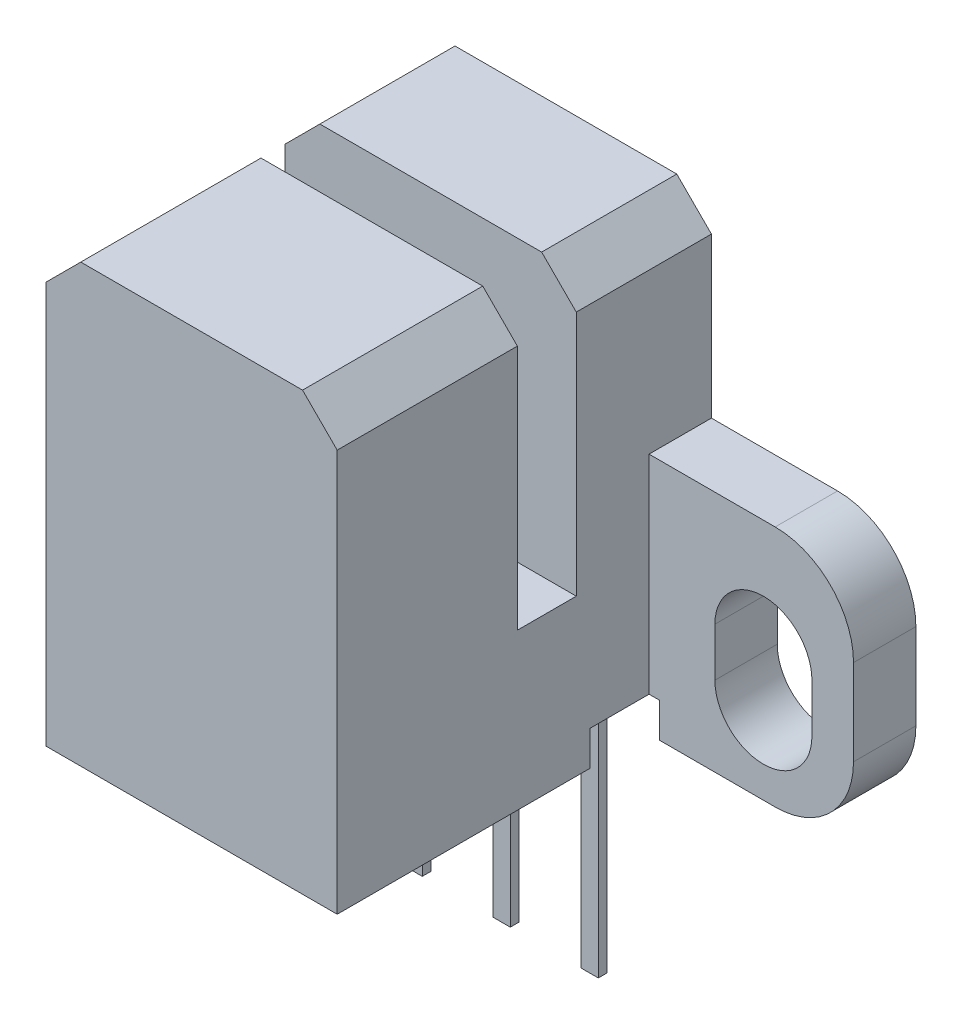
SolidWorks part; units mm, degrees
ref_plane "Front Plane" through (0, 0, 0) normal (0, 0, 1) x (1, 0, 0)
ref_plane "Top Plane" through (0, 0, 0) normal (0, 1, 0) x (1, 0, 0)
ref_plane "Right Plane" through (0, 0, 0) normal (1, 0, 0) x (0, 0, -1)
sketch "Sketch1" plane through (0, 0, 0) normal (0, 0, 1) x (1, 0, 0)
  line L0 (0, -8.7) -> (0, 3.9) construction
  line L1 (-4.2, -8.7) -> (4.2, -8.7)
  line L2 (-4.2, -8.7) -> (-4.2, 3.9)
  line L3 (-4.2, 3.9) -> (4.2, 3.9)
  line L4 (4.2, -8.7) -> (4.2, 3.9)
  dimension "D1" = 4.2
  dimension "D2" = 3.9
  dimension "D3" = 8.7
extrude "Boss-Extrude1" add sketch "Sketch1" along normal blind 10.8
chamfer "Chamfer1" distance 1 angle 45 2 edges at (-4.2, 3.9, 5.4) (4.2, 3.9, 5.4)
sketch "Sketch2" plane through (0, 0, 0) normal (0, 0, -1) x (-1, 0, 0)
  line L0 (4.2, -8.7) -> (-4.2, -8.7) construction
  line L1 (-7.84, -8.7) -> (7.84, -8.7)
  line L2 (-10.1, -6.44) -> (-10.1, -3.96)
  line L3 (-7.84, -1.7) -> (7.84, -1.7)
  line L4 (10.1, -6.44) -> (10.1, -3.96)
  line L5 (0, 0) -> (0, -8.7) construction
  line L6 (-7.5, -5) -> (-7.5, -6.4) construction
  line L7 (-6.1, -5) -> (-6.1, -6.4)
  line L8 (-8.9, -5) -> (-8.9, -6.4)
  line L9 (7.5, -5) -> (7.5, -6.4) construction
  line L10 (8.9, -5) -> (8.9, -6.4)
  line L11 (6.1, -5) -> (6.1, -6.4)
  line L12 (7.5, -5.7) -> (-7.5, -5.7) construction
  arc A0 (7.84, -8.7) -> (10.1, -6.44) centre (7.84, -6.44) ccw
  arc A1 (-10.1, -3.96) -> (-7.84, -1.7) centre (-7.84, -3.96) cw
  arc A2 (7.84, -1.7) -> (10.1, -3.96) centre (7.84, -3.96) cw
  arc A3 (-7.84, -8.7) -> (-10.1, -6.44) centre (-7.84, -6.44) cw
  arc A4 (-6.1, -5) -> (-8.9, -5) centre (-7.5, -5) ccw
  arc A5 (-8.9, -6.4) -> (-6.1, -6.4) centre (-7.5, -6.4) ccw
  arc A6 (8.9, -5) -> (6.1, -5) centre (7.5, -5) ccw
  arc A7 (6.1, -6.4) -> (8.9, -6.4) centre (7.5, -6.4) ccw
  point P13 (-10.1, -1.7)
  point P18 (-10.1, -8.7)
  point P21 (-7.5, -5.7)
  point P26 (7.5, -5.7)
  dimension "D3" = 2.26
  dimension "D5" = 5
  dimension "D1" = 20.2
  dimension "D2" = 7
  dimension "D4" = 15
  dimension "D6" = 1.4
  dimension "D7" = 2.8
extrude "Boss-Extrude2" add sketch "Sketch2" against normal blind 1.8
sketch "Sketch3" plane through (0, 3.9, 0) normal (0, 1, 0) x (1, 0, 0)
  line L0 (-4.2, -10.8) -> (-4.2, 0) construction
  line L1 (-4.2, -3.9) -> (4.2, -3.9)
  line L2 (-4.2, -3.9) -> (-4.2, -5.6)
  line L3 (-4.2, -5.6) -> (4.2, -5.6)
  line L4 (4.2, -3.9) -> (4.2, -5.6)
  line L6 (4.2, 0) -> (4.2, -10.8) construction
  line L7 (3.2, 0) -> (-3.2, 0) construction
  dimension "D1" = 1.7
  dimension "D2" = 3.9
extrude "Cut-Extrude1" cut sketch "Sketch3" against normal offset from surface (8.1 mm away) 4.2 up to plane "Top Plane" offset beyond the face yes
sketch "Sketch4" plane through (0, 0, 0) normal (0, 0, -1) x (-1, 0, 0)
  line L0 (0, -6.4) -> (0, 0) construction
  circle A0 centre (0, 0) radius 1
  circle A1 centre (0, -6.4) radius 1
  dimension "D1" = 2
  dimension "D2" = 6.4
extrude "Boss-Extrude3" add sketch "Sketch4" along normal blind 0.8
sketch "Sketch5" plane through (0, -8.7, 0) normal (0, -1, 0) x (1, 0, 0)
  line L0 (-7.84, 0) -> (7.84, 0) construction
  line L1 (-4.5, 0) -> (4.5, 0)
  line L2 (-4.5, 0) -> (-4.5, 3.5)
  line L3 (-4.5, 3.5) -> (4.5, 3.5)
  line L4 (4.5, 0) -> (4.5, 3.5)
  dimension "D1" = 9
  dimension "D2" = 3.5
extrude "Cut-Extrude2" cut sketch "Sketch5" against normal blind 1
ref_plane "Plane1" through (0, 0, 3) normal (0, 0, -1) x (-1, 0, 0)
sketch "Sketch6" plane through (0, 0, 3) normal (0, 0, -1) x (-1, 0, 0)
  line L0 (4.5, -7.7) -> (-4.5, -7.7) construction
  line L1 (-4.06, -7.7) -> (-3.56, -7.7)
  line L2 (-4.06, -7.7) -> (-4.06, -14.2)
  line L3 (-4.06, -14.2) -> (-3.56, -14.2)
  line L4 (-3.56, -7.7) -> (-3.56, -14.2)
  line L5 (0, 0) -> (0, -14.2) construction
  line L6 (-1.52, -7.7) -> (-1.02, -7.7)
  line L7 (-1.52, -7.7) -> (-1.52, -14.2)
  line L8 (-1.52, -14.2) -> (-1.02, -14.2)
  line L9 (-1.02, -7.7) -> (-1.02, -14.2)
  line L10 (1.02, -7.7) -> (1.52, -7.7)
  line L11 (1.02, -7.7) -> (1.02, -14.2)
  line L12 (1.02, -14.2) -> (1.52, -14.2)
  line L13 (1.52, -7.7) -> (1.52, -14.2)
  line L14 (3.56, -7.7) -> (4.06, -7.7)
  line L15 (3.56, -7.7) -> (3.56, -14.2)
  line L16 (3.56, -14.2) -> (4.06, -14.2)
  line L17 (4.06, -7.7) -> (4.06, -14.2)
  line L18 (-1.02, -14.2) -> (1.02, -14.2) construction
  line L19 (-4.5, -8.7) -> (-7.84, -8.7) construction
  line L20 (-1.52, -14.2) -> (-3.56, -14.2) construction
  dimension "D1" = 4
  dimension "D2" = 2.54
  dimension "D3" = 0.5
  dimension "D4" = 5.5
extrude "Boss-Extrude4" add sketch "Sketch6" along normal mid plane 0.25
